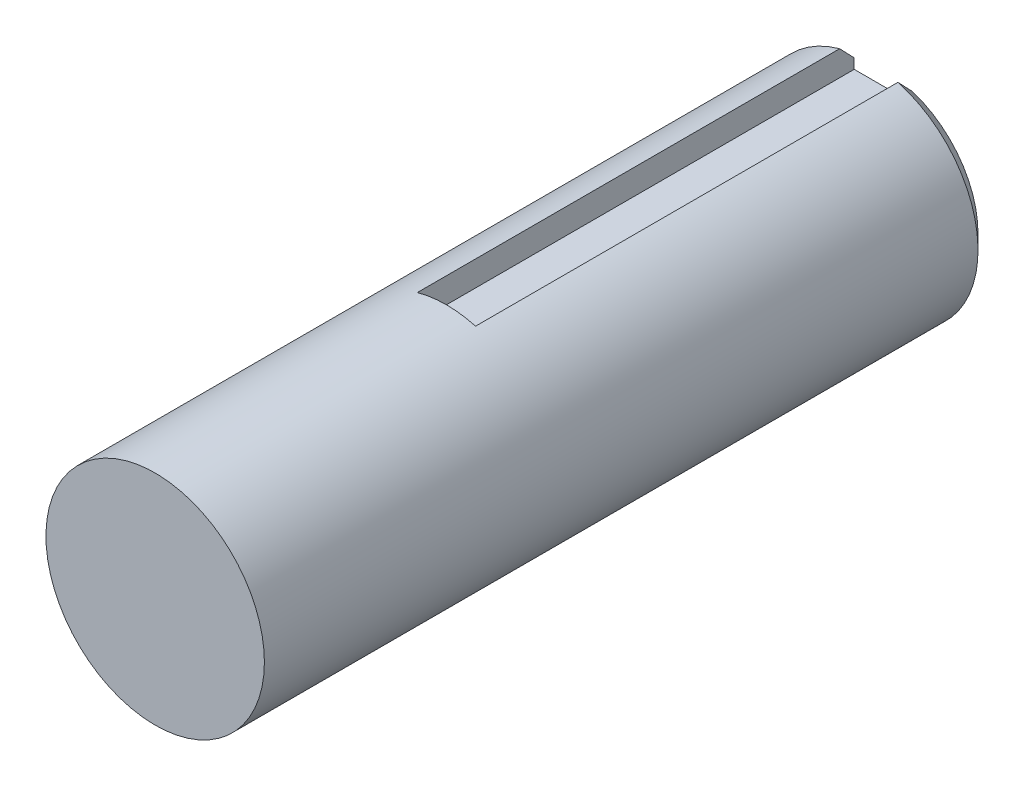
SolidWorks part; units mm, degrees
material "AISI 4130 Steel, normalized at 870C"
ref_plane "Front Plane" through (0, 0, 0) normal (0, 0, 1) x (1, 0, 0)
ref_plane "Top Plane" through (0, 0, 0) normal (0, 1, 0) x (1, 0, 0)
ref_plane "Right Plane" through (0, 0, 0) normal (1, 0, 0) x (0, 0, -1)
sketch "Sketch1" plane through (0, 0, 0) normal (0, 0, 1) x (1, 0, 0)
  circle A0 centre (0, 0) radius 15
extrude "Boss-Extrude1" add sketch "Sketch1" along normal blind 100
chamfer "Chamfer1" distance 2 angle 45 1 edges at (15, 0, 0)
sketch "Sketch2" plane through (0, 0, 100) normal (0, 0, 1) x (1, 0, 0)
  line L0 (0, 0) -> (0, 15)
  circle A0 centre (0, 0) radius 15 construction
ref_plane "Plane1" through (0, 15, 100) normal (0, 1, 0) x (1, 0, 0)
sketch "Sketch3" plane through (0, 15, 100) normal (0, 1, 0) x (1, 0, 0)
  line L0 (13, 100) -> (-13, 100) construction
  line L1 (-4, 100) -> (4, 100)
  line L2 (-4, 100) -> (-4, 40)
  line L3 (-4, 40) -> (4, 40)
  line L4 (4, 100) -> (4, 40)
  line L5 (0, 0) -> (0, 98) construction
  dimension "D1" = 4
extrude "Cut-Extrude1" cut sketch "Sketch3" against normal blind 4
fillet "Fillet1" radius 3 1 edges at (0, 11, 60)
scale "Escala1" scale about centroid uniform scaling yes scale factor 0.5
